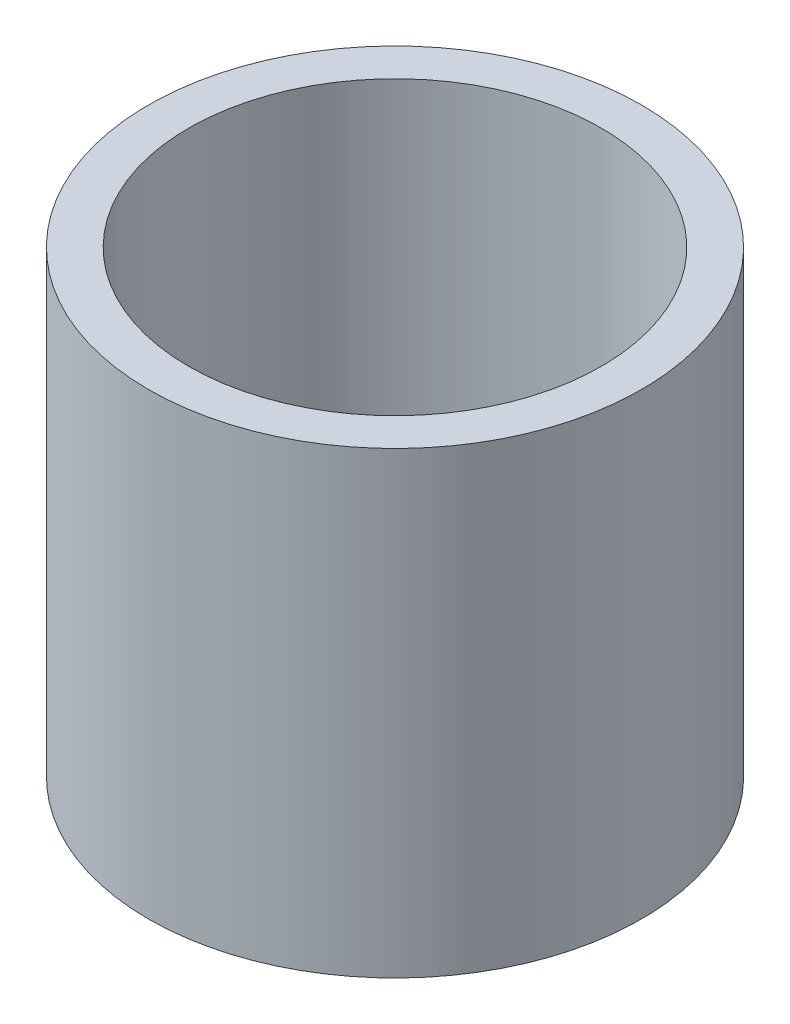
SolidWorks part; units mm, degrees
ref_plane "Front Plane" through (0, 0, 0) normal (0, 0, 1) x (1, 0, 0)
ref_plane "Top Plane" through (0, 0, 0) normal (0, 1, 0) x (1, 0, 0)
ref_plane "Right Plane" through (0, 0, 0) normal (1, 0, 0) x (0, 0, -1)
sketch "Sketch1" plane through (0, 0, 0) normal (0, 1, 0) x (1, 0, 0)
  circle A0 centre (0, 0) radius 2.15
  dimension "D1" = 4.3
extrude "Boss-Extrude1" add sketch "Sketch1" along normal blind 4
hole_wizard "M3 Clearance Hole1" positions "Sketch3" profile "Sketch2" hole size "M3" standard "ISO" end condition through all
sketch "Sketch3" plane through (0, 4, 0) normal (0, 1, 0) x (1, 0, 0)
  point P0 (0, 0)
sketch "Sketch2" plane through (0, 4, 0) normal (1, 0, 0) x (0, 0, 1)
  line L0 (0, 0) -> (0, 4)
  line L1 (0, 4) -> (1.8, 4)
  line L2 (1.8, 4) -> (1.8, 0)
  line L5 (1.8, 0) -> (0, 0)
  line L11 (0, -6.35) -> (0, 107.95) construction
  dimension "Thru Hole Dia." = 3.6
  dimension "Thru Hole Depth" = 4
